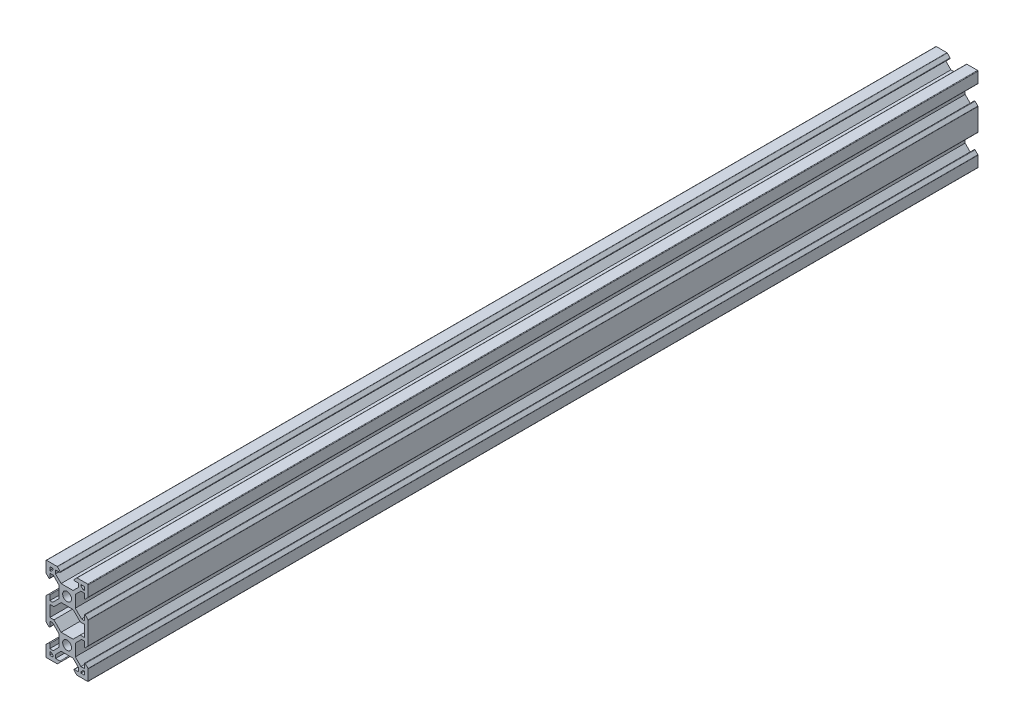
SolidWorks part; units mm, degrees
material "1060 Alloy"
ref_plane "Front Plane" through (0, 0, 0) normal (0, 0, 1) x (1, 0, 0)
ref_plane "Top Plane" through (0, 0, 0) normal (0, 1, 0) x (1, 0, 0)
ref_plane "Right Plane" through (0, 0, 0) normal (1, 0, 0) x (0, 0, -1)
sketch "Sketch1" plane through (0, 0, 0) normal (0, 0, 1) x (1, 0, 0)
  line L0 (8.2, -10) -> (10, -10)
  line L2 (10, -10) -> (10, -4.64)
  line L3 (10, -4.64) -> (8.2, -2.84)
  line L4 (8.2, -2.84) -> (8.2, -5.8007)
  line L5 (8.2, -5.8007) -> (6.8613, -5.8007)
  line L6 (6.8613, -5.8007) -> (3.9007, -2.84)
  line L7 (3.9007, -2.84) -> (3.9007, 2.84)
  line L8 (3.9007, 2.84) -> (6.56, 5.4993)
  line L9 (6.56, 5.4993) -> (8.2, 5.4993)
  line L10 (8.2, 5.4993) -> (8.2, 2.84)
  line L11 (8.2, 2.84) -> (10, 4.64)
  line L12 (10, 4.64) -> (10, 10)
  line L13 (10, 10) -> (4.64, 10)
  line L14 (4.64, 10) -> (2.84, 8.2)
  line L15 (2.84, 8.2) -> (5.4993, 8.2)
  line L16 (5.4993, 8.2) -> (5.4993, 6.56)
  line L17 (5.4993, 6.56) -> (2.84, 3.9007)
  line L18 (2.84, 3.9007) -> (-2.84, 3.9007)
  line L19 (-2.84, 3.9007) -> (-5.4993, 6.56)
  line L20 (-5.4993, 6.56) -> (-5.4993, 8.2)
  line L21 (-5.4993, 8.2) -> (-2.84, 8.2)
  line L22 (-2.84, 8.2) -> (-4.64, 10)
  line L23 (-4.64, 10) -> (-10, 10)
  line L24 (-10, 10) -> (-10, 4.64)
  line L25 (-10, 4.64) -> (-8.2, 2.84)
  line L26 (-8.2, 2.84) -> (-8.2, 5.4993)
  line L27 (-8.2, 5.4993) -> (-6.56, 5.4993)
  line L28 (-6.56, 5.4993) -> (-3.9007, 2.84)
  line L29 (-3.9007, 2.84) -> (-3.9007, -2.84)
  line L30 (-3.9007, -2.84) -> (-6.8613, -5.8007)
  line L31 (-6.8613, -5.8007) -> (-8.2, -5.8007)
  line L32 (-8.2, -5.8007) -> (-8.2, -2.84)
  line L33 (-8.2, -2.84) -> (-10, -4.64)
  line L34 (-10, -4.64) -> (-10, -10)
  line L64 (8.2, -7.3007) -> (8.2, -10)
  line L70 (-8.2, -10) -> (-8.2, -7.3007)
  line L71 (-8.2, -7.3007) -> (-6.24, -7.3007)
  line L72 (-6.24, -7.3007) -> (-2.84, -3.9007)
  line L73 (-2.84, -3.9007) -> (2.84, -3.9007)
  line L74 (2.84, -3.9007) -> (6.24, -7.3007)
  line L75 (6.24, -7.3007) -> (8.2, -7.3007)
  line L76 (-10, -10) -> (-8.2, -10)
  circle A0 centre (0, 0) radius 2.1
  point P46 (0, -3.9007)
  point P47 (0, 3.9007)
  point P49 (-3.9007, 0)
  point P50 (3.9007, 0)
  dimension "D1" = 4.2
  dimension "D8" = 1.8
  dimension "D2" = 20
  dimension "D3" = 20
  dimension "D4" = 5.68
  dimension "D5" = 90
  dimension "D6" = 10
  dimension "D7" = 10
  dimension "D9" = 1.8
  dimension "D10" = 1.8
  dimension "D11" = 1.5
  dimension "D12" = 1.5
  dimension "D13" = 1.64
  dimension "D14" = 1.5
  dimension "D15" = 1.96
extrude "Boss-Extrude2" add sketch "Sketch1" along normal blind 422
sketch "Sketch2" plane through (0, 0, 422) normal (0, 0, 1) x (1, 0, 0)
  line L0 (-8.2, 2.84) -> (-8.2, 5.4993) construction
  line L1 (-5.4993, 8.2) -> (-2.84, 8.2) construction
  line L2 (-8.2, 6.5693) -> (-8.2, 8.2)
  line L3 (-8.2, 8.2) -> (-6.5693, 8.2)
  line L4 (8.2, 5.4993) -> (8.2, 2.84) construction
  line L5 (8.2, 8.2) -> (8.2, 6.5693)
  line L6 (3.9007, 2.84) -> (6.56, 5.4993) construction
  line L7 (-5.4993, 6.56) -> (-5.4993, 8.2) construction
  line L8 (6.56, 5.4993) -> (8.2, 5.4993) construction
  line L11 (6.5693, 8.2) -> (6.5693, 6.56)
  line L12 (6.5693, 8.2) -> (6.5693, 7.63)
  line L16 (6.5693, 8.2) -> (8.2, 8.2)
  line L17 (-8.2, 6.5693) -> (-6.56, 6.5693)
  line L18 (-8.2, 6.5693) -> (-7.63, 6.5693)
  line L19 (-7.63, 6.5693) -> (-6.5693, 7.63)
  line L20 (6.5693, 7.63) -> (7.63, 6.5693)
  line L22 (7.63, 6.5693) -> (8.2, 6.5693)
  line L24 (-6.5693, 7.63) -> (-6.5693, 8.2)
  dimension "D5" = 1.5
  dimension "D1" = 1.07
  dimension "D3" = 1.07
  dimension "D2" = 1.07
  dimension "D4" = 1.07
extrude "Cut-Extrude1" cut sketch "Sketch2" against normal through all
fillet "Fillet1" radius 0.25 14 edges at (8.2, 2.84, 211) (-10, 4.64, 211) (-4.64, 10, 211) (4.64, 10, 211) (-10, -4.64, 211) (-10, 10, 211) (10, -4.64, 211) (10, 10, 211) (8.2, -2.84, 211) (-8.2, -2.84, 211) (-8.2, 2.84, 211) (10, 4.64, 211) (2.84, 8.2, 211) (-2.84, 8.2, 211)
ref_plane "Plane1" through (0, -10, 0) normal (0, -1, 0) x (-1, 0, 0)
mirror "Mirror1" about plane through (0, -10, 0) normal (0, -1, 0) of "Fillet1", "Boss-Extrude2"
mirror "Mirror2" about plane through (0, -10, 0) normal (0, -1, 0) of "Cut-Extrude1"
